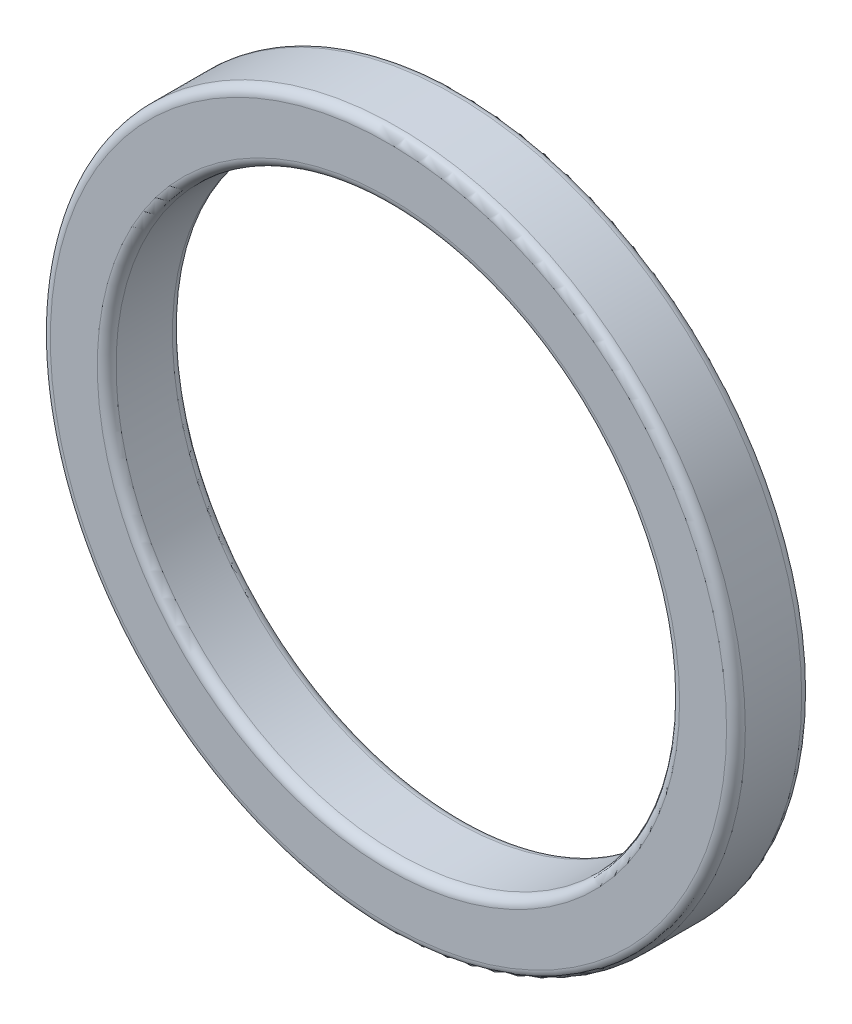
SolidWorks part; units mm, degrees
ref_plane "前视基准面" through (0, 0, 0) normal (0, 0, 1) x (1, 0, 0)
ref_plane "上视基准面" through (0, 0, 0) normal (0, 1, 0) x (1, 0, 0)
ref_plane "右视基准面" through (0, 0, 0) normal (1, 0, 0) x (0, 0, -1)
other "Configuration Table"
sketch "草图1" plane through (0, 0, 0) normal (0, 0, 1) x (1, 0, 0)
  circle A0 centre (0, 0) radius 15
  circle A1 centre (0, 0) radius 18.5
  dimension "D1" = 30
  dimension "D2" = 37
extrude "凸台-拉伸1" add sketch "草图1" along normal blind 4
fillet "圆角1" radius 0.5 4 edges at (15, 0, 0) (18.5, 0, 0) (15, 0, 4) (18.5, 0, 4)
